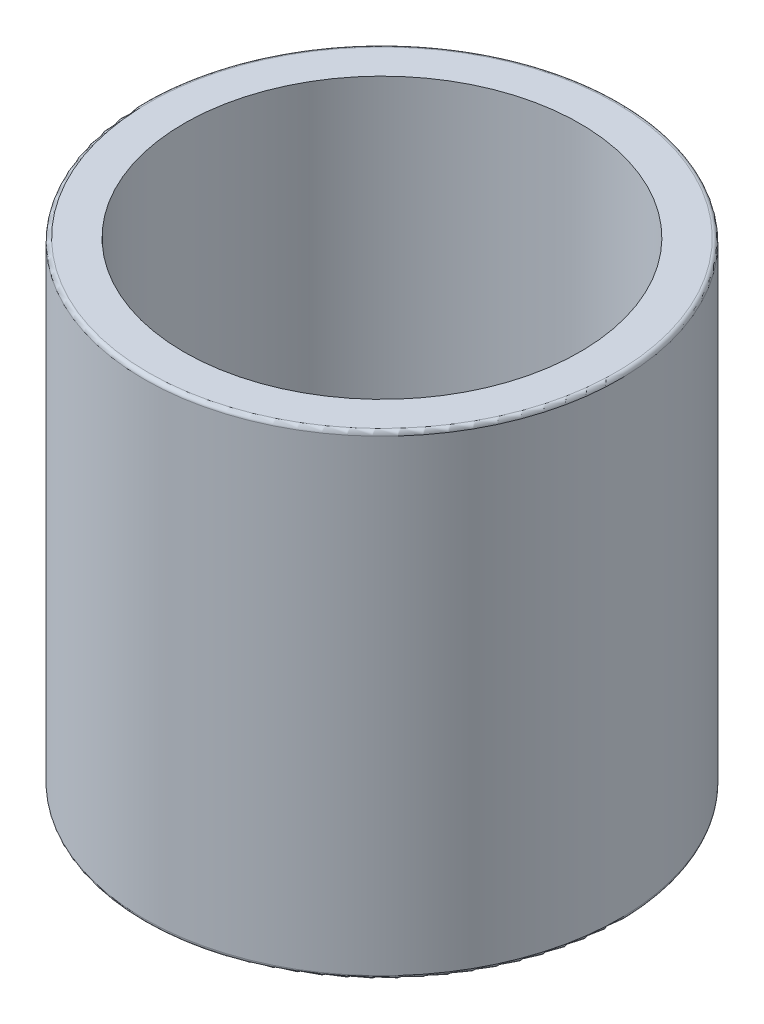
SolidWorks part; units mm, degrees
material "ABS"
ref_plane "Ebene vorne" through (0, 0, 0) normal (0, 0, 1) x (1, 0, 0)
ref_plane "Ebene oben" through (0, 0, 0) normal (0, 1, 0) x (1, 0, 0)
ref_plane "Ebene rechts" through (0, 0, 0) normal (1, 0, 0) x (0, 0, -1)
sketch "Skizze1" plane through (0, 0, 0) normal (0, 1, 0) x (1, 0, 0)
  circle A0 centre (0, 0) radius 5
  circle A1 centre (0, 0) radius 6
  dimension "D1" = 10
  dimension "D2" = 1
extrude "Aufsatz-Linear austragen1" add sketch "Skizze1" along normal mid plane 12
fillet "Verrundung1" radius 0.1 2 edges at (0, -6, 6) (0, 6, 6)
